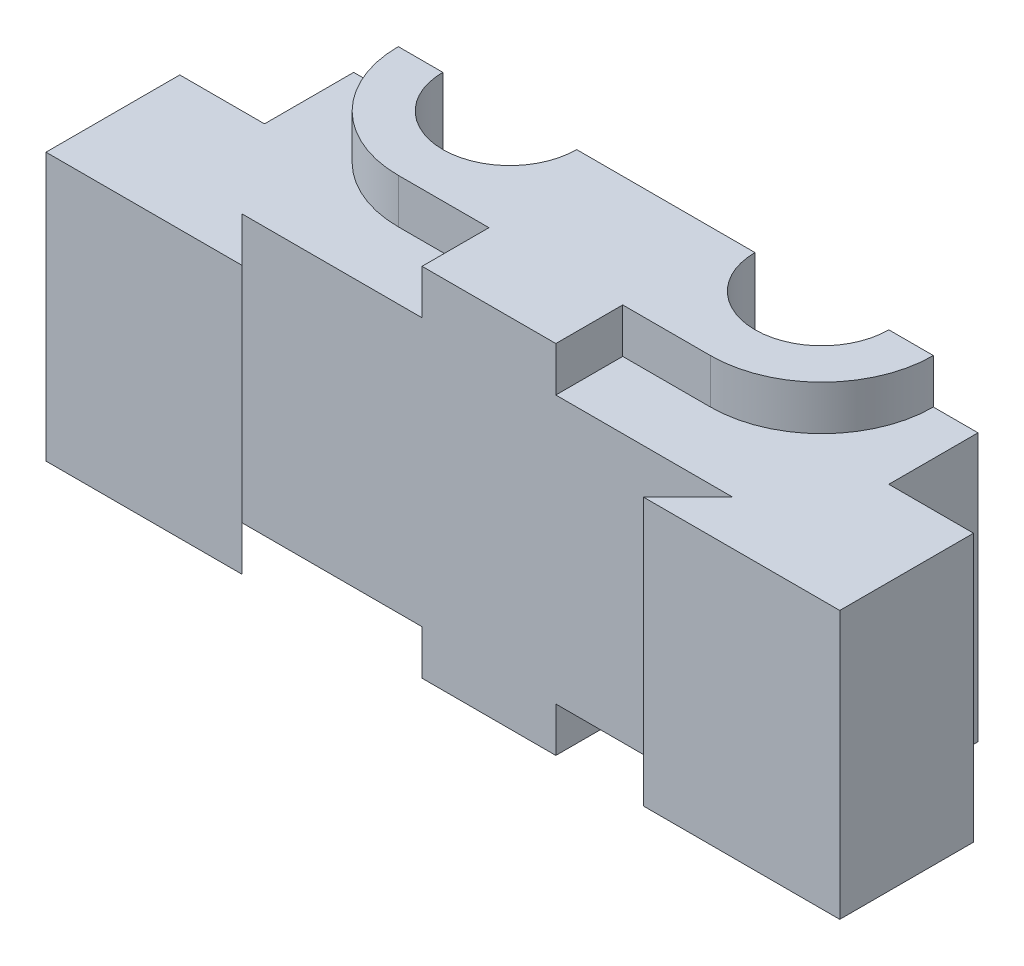
SolidWorks part; units mm, degrees
ref_plane "Front Plane" through (0, 0, 0) normal (0, 0, 1) x (1, 0, 0)
ref_plane "Top Plane" through (0, 0, 0) normal (0, 1, 0) x (1, 0, 0)
ref_plane "Right Plane" through (0, 0, 0) normal (1, 0, 0) x (0, 0, -1)
sketch "Sketch1" plane through (0, 0, 0) normal (0, 1, 0) x (1, 0, 0)
  line L0 (0, 0) -> (-27.5, 0)
  line L1 (0, 0) -> (27.5, 0)
  line L2 (-27.5, 0) -> (-22.5, -5)
  line L3 (-22.5, -5) -> (-44.5, -5)
  line L4 (-44.5, -5) -> (-44.5, 10)
  line L5 (-44.5, 10) -> (-35, 10)
  line L6 (-35, 10) -> (-35, 20)
  line L7 (-35, 20) -> (-25, 20)
  line L8 (-10, 20) -> (10, 20)
  line L9 (25, 20) -> (35, 20)
  line L10 (35, 20) -> (35, 10)
  line L11 (35, 10) -> (44.5, 10)
  line L12 (44.5, 10) -> (44.5, -5)
  line L13 (44.5, -5) -> (22.5, -5)
  line L14 (22.5, -5) -> (27.5, 0)
  arc A0 (-25, 20) -> (-10, 20) centre (-17.5, 20) ccw
  arc A1 (10, 20) -> (25, 20) centre (17.5, 20) ccw
  dimension "D1" = 7.5
  dimension "D2" = 15
  dimension "D3" = 17.5
  dimension "D4" = 35
  dimension "D5" = 5
  dimension "D6" = 45
  dimension "D7" = 22
  dimension "D8" = 10
  dimension "D9" = 5
extrude "Boss-Extrude1" add sketch "Sketch1" along normal mid plane 30
sketch "Sketch2" plane through (0, 0, 0) normal (0, 1, 0) x (1, 0, 0)
  line L0 (-30, 20) -> (-25, 20)
  line L1 (-10, 20) -> (5, 20)
  line L2 (30, 20) -> (25, 20)
  line L3 (10, 20) -> (5, 20)
  line L10 (-7.3354, 7.5) -> (-7.3354, 0)
  line L11 (-27.5, 0) -> (27.5, 0) construction
  line L12 (-7.3354, 0) -> (7.6646, 0)
  line L13 (7.6646, 0) -> (7.6646, 7.5)
  line L14 (-7.3354, 7.5) -> (-17.5, 7.5)
  line L15 (17.5, 7.5) -> (7.6646, 7.5)
  arc A0 (-30, 20) -> (-17.5, 7.5) centre (-17.5, 20) ccw
  arc A1 (17.5, 7.5) -> (30, 20) centre (17.5, 20) ccw
  arc A2 (-25, 20) -> (-10, 20) centre (-17.5, 20) ccw
  arc A3 (25, 20) -> (10, 20) centre (17.5, 20) cw
  dimension "D1" = 25
  dimension "D2" = 15
extrude "Boss-Extrude2" add sketch "Sketch2" along normal mid plane 40
sketch "Sketch3" plane through (0, 0, -20) normal (0, 0, -1) x (-1, 0, 0)
  line L0 (0, 20) -> (0, -20) construction
  line L1 (-10, 20) -> (10, 20) construction
  line L2 (-10, -20) -> (10, -20) construction
  line L3 (-44.5, 0) -> (44.5, 0) construction
  line L4 (-44.5, 15) -> (-44.5, -15) construction
  line L5 (44.5, 15) -> (44.5, -15) construction
  line L6 (-35, 15) -> (-30, 15) construction
  circle A0 centre (0, 15) radius 2.25
  circle A1 centre (-30, 7.5) radius 2.25
  circle A2 centre (-30, -7.5) radius 2.25
  circle A3 centre (30, -7.5) radius 2.25
  circle A4 centre (30, 7.5) radius 2.25
  circle A5 centre (0, -15) radius 2.25
  dimension "D1" = 4.5
  dimension "D2" = 30
  dimension "D3" = 15
  dimension "D4" = 7.5
  dimension "D5" = 7.5
  dimension "D6" = 5
extrude "Cut-Extrude1" cut sketch "Sketch3" against normal blind 15
